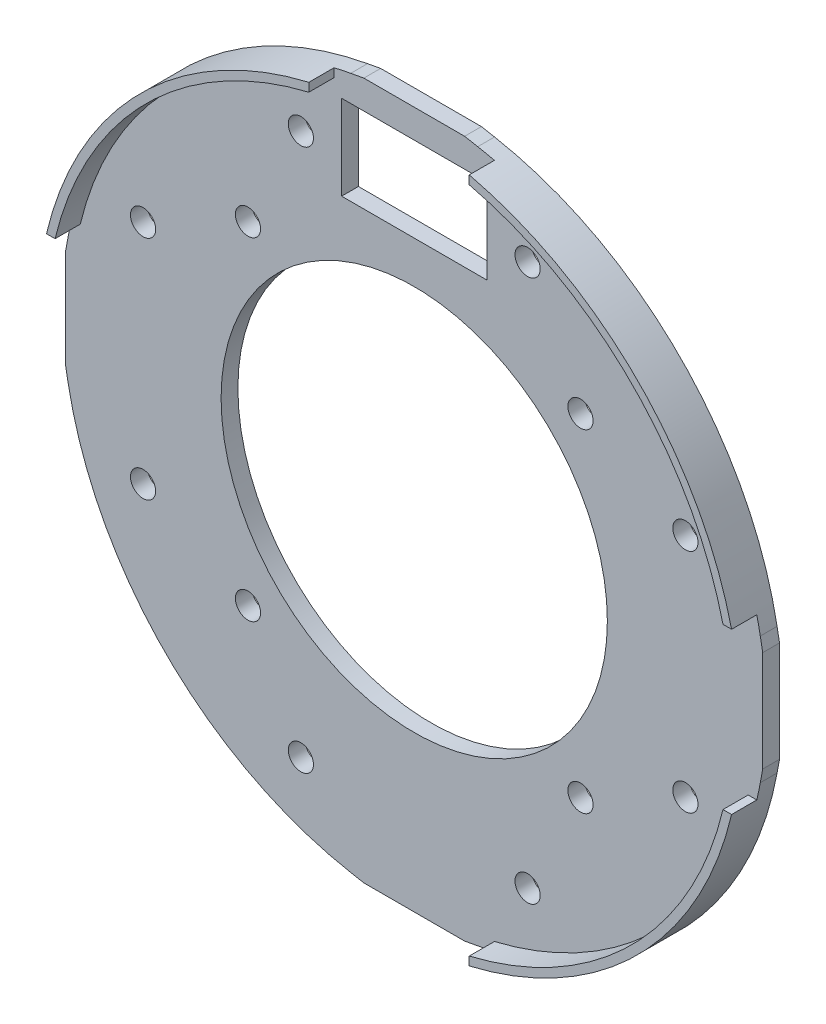
SolidWorks part; units mm, degrees
ref_plane "Спереди" through (0, 0, 0) normal (0, 0, 1) x (1, 0, 0)
ref_plane "Сверху" through (0, 0, 0) normal (0, 1, 0) x (1, 0, 0)
ref_plane "Справа" through (0, 0, 0) normal (1, 0, 0) x (0, 0, -1)
ref_plane "Плоскость4" through (0, 0, -2) normal (0, 0, 1) x (1, 0, 0)
sketch "Эскиз1" plane through (0, 0, -2) normal (0, 0, 1) x (1, 0, 0)
  line L0 (41.5, 6) -> (35.9512, 35.9512)
  line L1 (35.9512, 35.9512) -> (6, 41.5)
  line L2 (6, 41.5) -> (-6, 41.5)
  line L3 (-6, 41.5) -> (-35.9512, 35.9512)
  line L4 (-35.9512, 35.9512) -> (-41.5, 6)
  line L5 (-41.5, 6) -> (-41.5, -6)
  line L6 (-41.5, -6) -> (-35.9512, -35.9512)
  line L7 (-35.9512, -35.9512) -> (-6, -41.5)
  line L8 (-6, -41.5) -> (6, -41.5)
  line L9 (6, -41.5) -> (35.9512, -35.9512)
  line L10 (35.9512, -35.9512) -> (41.5, -6)
  line L11 (41.5, -6) -> (41.5, 6)
extrude "Бобышка-Вытянуть1" add sketch "Эскиз1" against normal blind 2
hole_wizard "Диаметр отверстия Ø3.0 (3)1" positions "Эскиз7" profile "Эскиз6" hole size "Ø3.0" standard "Ansi Metric"
sketch "Эскиз7" plane through (0, 0, -2) normal (0, 0, 1) x (1, 0, 0)
  point P0 (32.2916, -13.5)
  point P1 (32.2916, 13.5)
  point P2 (19.799, 19.799)
  point P3 (19.799, -19.799)
  point P4 (13.5, -32.2916)
  point P5 (-13.5, -32.2916)
  point P6 (-19.799, -19.799)
  point P7 (-19.799, 19.799)
  point P8 (-13.5, 32.2916)
  point P9 (13.5, 32.2916)
  point P10 (-32.2916, 13.5)
  point P11 (-32.2916, -13.5)
sketch "Эскиз6" plane through (32.2916, -13.5, -2) normal (1, 0, 0) x (0, -1, 0)
  line L0 (0, 0) -> (0, 2)
  line L1 (0, 2) -> (1.5, 2)
  line L2 (1.5, 2) -> (1.5, 0)
  line L5 (1.5, 0) -> (0, 0)
  line L11 (0, -6.35) -> (0, 107.95) construction
  dimension "Диаметр сквозного отверстия" = 3
  dimension "Глубина сквозного отверстия" = 2
hole_wizard "Отверстие с зазором M421" positions "Эскиз9" profile "Эскиз8" hole size "M42" standard "Ansi Metric"
sketch "Эскиз9" plane through (0, 0, -2) normal (0, 0, 1) x (1, 0, 0)
  point P0 (0, 0)
sketch "Эскиз8" plane through (0, 0, -2) normal (1, 0, 0) x (0, -1, 0)
  line L0 (0, 0) -> (0, 2)
  line L1 (0, 2) -> (23, 2)
  line L2 (23, 2) -> (23, 0)
  line L5 (23, 0) -> (0, 0)
  line L11 (0, -6.35) -> (0, 107.95) construction
  dimension "Диаметр сквозного отверстия" = 46
  dimension "Глубина сквозного отверстия" = 2
fillet "Скругление1" radius 42 4 edges at (35.9512, 35.9512, -3) (-35.9512, 35.9512, -3) (35.9512, -35.9512, -3) (-35.9512, -35.9512, -3)
sketch "Эскиз10" plane through (0, 0, -2) normal (0, 0, 1) x (1, 0, 0)
  line L0 (-9.5499, 40.8999) -> (-9.5499, 9.5499)
  line L1 (-9.5499, 9.5499) -> (-40.8999, 9.5499)
  circle A0 centre (0, 0) radius 40.9
  circle A1 centre (0, 0) radius 42
  arc M19 (-7.5638, 41.2103) -> (-41.2103, 7.5638) centre (0.087, -0.087) ccw
  dimension "D1" = 81.8
  dimension "D4" = 84
  dimension "D2" = 31.35
  dimension "D3" = 31.35
extrude "Бобышка-Вытянуть2" add sketch "Эскиз10" along normal blind 3 contours A0 L0 L1 M19
pattern_circular "Круговой массив1" count 3 every 90 about axis through (0, 0, 0) along (0, 0, 1) of "Бобышка-Вытянуть2"
sketch "Эскиз12" plane through (0, 0, -4) normal (0, 0, -1) x (-1, 0, 0)
  line L1 (-8.645, 38.1) -> (8.645, 38.1)
  line L2 (-8.645, 38.1) -> (-8.645, 28)
  line L3 (-8.645, 28) -> (8.645, 28)
  line L4 (8.645, 38.1) -> (8.645, 28)
  dimension "D1" = 17.29
  dimension "D2" = 10.1
  dimension "D3" = 8.645
  dimension "D4" = 28
extrude "Вырез-Вытянуть2" cut sketch "Эскиз12" against normal blind 10 contours L2 L3 L4 L1
